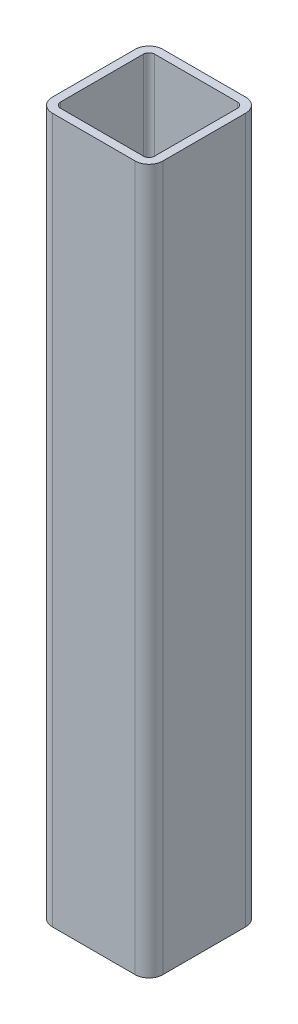
SolidWorks part; units mm, degrees
ref_plane "Front Plane" through (0, 0, 0) normal (0, 0, 1) x (1, 0, 0)
ref_plane "Top Plane" through (0, 0, 0) normal (0, 1, 0) x (1, 0, 0)
ref_plane "Right Plane" through (0, 0, 0) normal (1, 0, 0) x (0, 0, -1)
sketch "Sketch1" plane through (0, 0, 0) normal (0, 1, 0) x (1, 0, 0)
  line L1 (-15, -20) -> (15, -20)
  line L2 (-20, -15) -> (-20, 15)
  line L3 (-15, 20) -> (15, 20)
  line L4 (20, -15) -> (20, 15)
  line L5 (-20, -20) -> (20, 20) construction
  line L6 (-20, 20) -> (20, -20) construction
  arc A0 (-20, -15) -> (-15, -20) centre (-15, -15) ccw
  arc A1 (15, -20) -> (20, -15) centre (15, -15) ccw
  arc A2 (20, 15) -> (15, 20) centre (15, 15) ccw
  arc A3 (-15, 20) -> (-20, 15) centre (-15, 15) ccw
  point P0 (0, 0)
  point P18 (0, 0)
  point P19 (0, -20)
  point P20 (0, 20)
  point P21 (0, 0)
  point P22 (0, 0)
  point P23 (20, 0)
  point P24 (-20, 0)
  dimension "D1" = 5
  dimension "D2" = 40
extrude "Extrude-Thin1" add sketch "Sketch1" along normal mid plane 255 thin thin type one direction reverse wall 3
